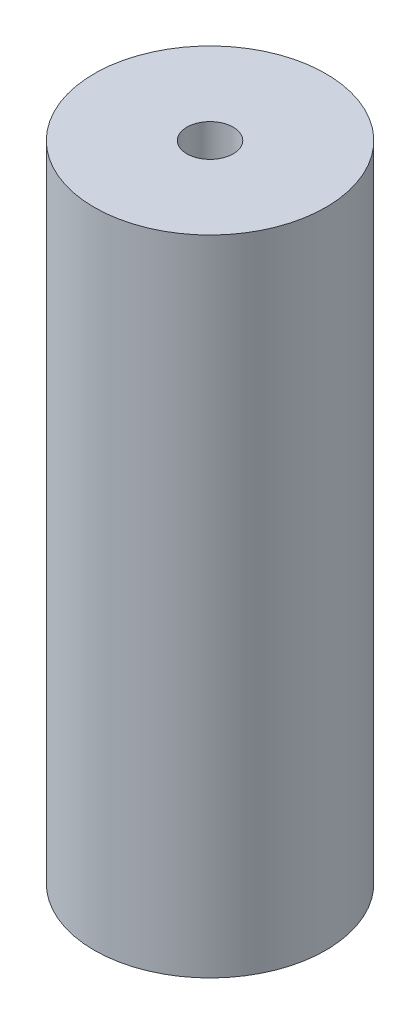
SolidWorks part; units mm, degrees
ref_plane "Front Plane" through (0, 0, 0) normal (0, 0, 1) x (1, 0, 0)
ref_plane "Top Plane" through (0, 0, 0) normal (0, 1, 0) x (1, 0, 0)
ref_plane "Right Plane" through (0, 0, 0) normal (1, 0, 0) x (0, 0, -1)
sketch "Sketch1" plane through (0, 0, 0) normal (0, 1, 0) x (1, 0, 0)
  circle A0 centre (0, 0) radius 4.5
  circle A1 centre (0, 0) radius 2.05
  dimension "D1" = 9
  dimension "D2" = 4.1
extrude "Boss-Extrude1" add sketch "Sketch1" along normal blind 10
sketch "Sketch3" plane through (0, 10, 0) normal (0, 1, 0) x (1, 0, 0)
  circle A1 centre (0, 0) radius 4.5
  circle A2 centre (0, 0) radius 0.9
  circle A3 centre (0, 0) radius 4.5 construction
  dimension "D1" = 1.8
extrude "Boss-Extrude3" add sketch "Sketch3" along normal blind 15
